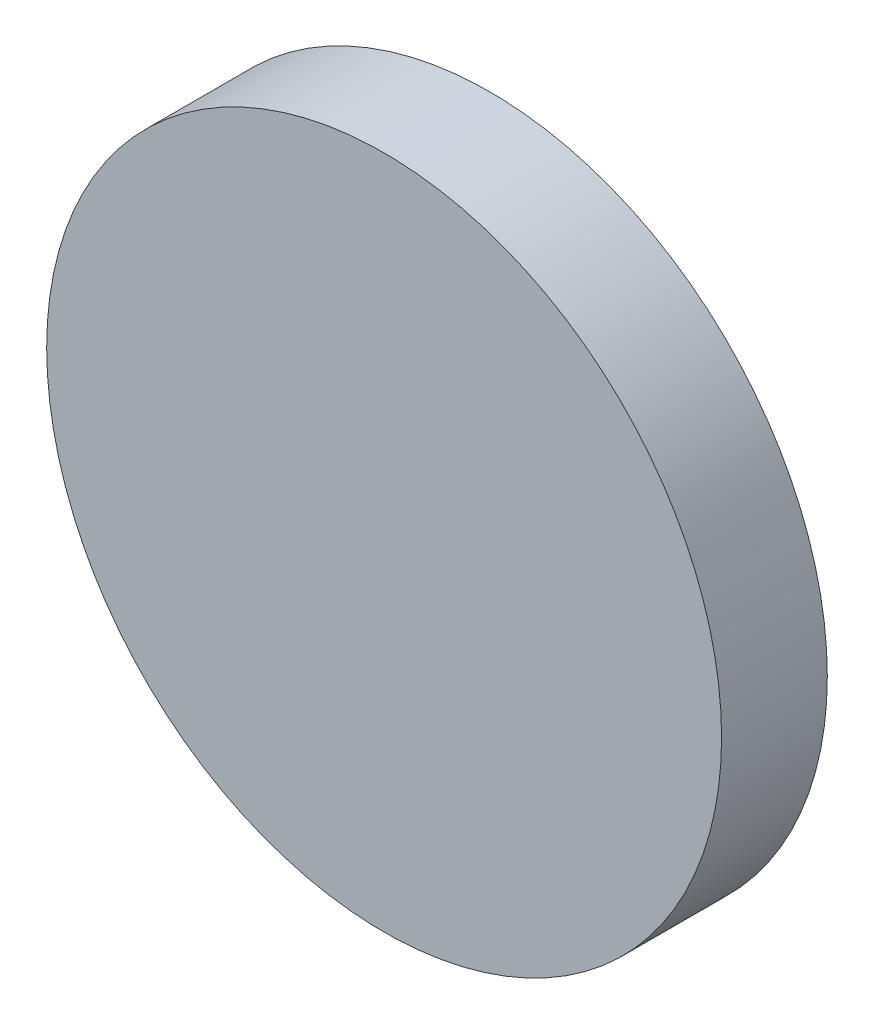
SolidWorks part; units mm, degrees
ref_plane "Plan de face" through (0, 0, 0) normal (0, 0, 1) x (1, 0, 0)
ref_plane "Plan de dessus" through (0, 0, 0) normal (0, 1, 0) x (1, 0, 0)
ref_plane "Plan de droite" through (0, 0, 0) normal (1, 0, 0) x (0, 0, -1)
sketch "Esquisse1" plane through (0, 0, 0) normal (0, 0, 1) x (1, 0, 0)
  circle A0 centre (0, 0) radius 15
  dimension "D1" = 30
extrude "Boss.-Extru.1" add sketch "Esquisse1" along normal blind 4.7
